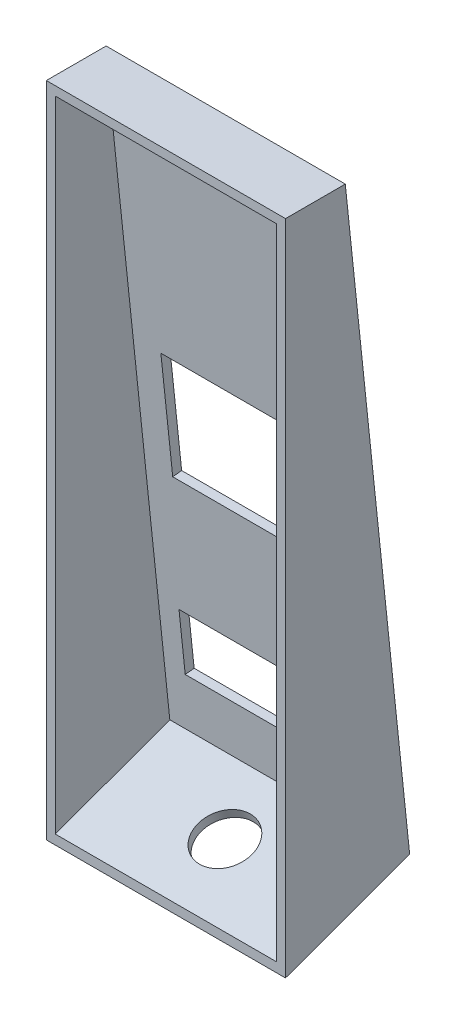
SolidWorks part; units mm, degrees
ref_plane "Front Plane" through (0, 0, 0) normal (0, 0, 1) x (1, 0, 0)
ref_plane "Top Plane" through (0, 0, 0) normal (0, 1, 0) x (1, 0, 0)
ref_plane "Right Plane" through (0, 0, 0) normal (1, 0, 0) x (0, 0, -1)
sketch "Sketch2" plane through (0, 0, 0) normal (0, 0, 1) x (1, 0, 0)
  line L1 (0, -2930) -> (-400, -2930)
  line L2 (0, -2930) -> (0, -4030)
  line L3 (0, -4030) -> (-400, -4030)
  line L4 (-400, -2930) -> (-400, -4030)
  point P4 (-250, 505)
  point P7 (0, 0)
  point P8 (0, 0)
  point P9 (0, 0)
sketch "Sketch3" plane through (0, -2930, 0) normal (0, 1, 0) x (1, 0, 0)
  line L0 (0, -300) -> (0, 0) construction
  line L1 (-400, -300) -> (0, -300)
  line L2 (-400, -300) -> (-400, 100)
  line L3 (-400, 100) -> (0, 100)
  line L4 (0, -300) -> (0, 100)
  line L5 (-400, -300) -> (0, 100) construction
  line L6 (-400, 100) -> (0, -300) construction
  point P4 (-200, -100)
  dimension "D1" = 400
sketch "Sketch5" plane through (0, 0, 0) normal (0, 0, -1) x (-1, 0, 0)
  line L0 (400, -2930) -> (400, -4030) construction
  line L1 (0, -2930) -> (400, -2930)
  line L2 (0, -2930) -> (0, -3880)
  line L3 (0, -3880) -> (400, -3880)
  line L4 (400, -2930) -> (400, -3880)
  line L5 (0, -2930) -> (400, -3880) construction
  line L6 (0, -3880) -> (400, -2930) construction
  point P4 (200, -3405)
  dimension "D1" = 950
ref_plane "Plane1" through (0, -21.6182, 205.6832) normal (0, 0.1045, -0.9945) x (1, 0, 0)
sketch "Sketch4" plane through (0, -21.6182, 205.6832) normal (0, 0.1045, -0.9945) x (1, 0, 0)
  line L0 (-400, 2913.9492) -> (-400, 4007.9232) construction
  line L1 (0, 2924.402) -> (-400, 2924.402)
  line L2 (0, 2924.402) -> (0, 3954.402)
  line L3 (0, 3954.402) -> (-400, 3954.402)
  line L4 (-400, 2924.402) -> (-400, 3954.402)
  line L7 (0, 2913.9492) -> (0, 4007.9232) construction
  line L8 (-400, 2924.402) -> (0, 2924.402) construction
  point P4 (-200, -616.3498)
  point P5 (0, -112.6957)
  point P6 (0, 0)
  point P7 (0, 0)
  point P8 (0, 0)
  point P15 (0, 0)
  point P16 (-385, 1118.8822)
  dimension "D1" = 1030
loft "Loft1" add profiles "Sketch4", "Sketch2"
sketch "Sketch6" plane through (0, -21.6182, 205.6832) normal (0, 0.1045, -0.9945) x (-1, 0, 0)
  line L0 (200, 53.5212) -> (200, 50053.5212) construction
  line L1 (51.5, -3344.402) -> (348.5, -3344.402) construction
  line L2 (51.5, -3344.402) -> (51.5, -3554.402) construction
  line L3 (51.5, -3554.402) -> (348.5, -3554.402) construction
  line L4 (348.5, -3344.402) -> (348.5, -3554.402) construction
  line L5 (50, -3854.402) -> (350, -3854.402)
  line L6 (50, -3854.402) -> (50, -3754.402)
  line L7 (61.5, -3354.402) -> (338.5, -3354.402)
  line L8 (61.5, -3354.402) -> (61.5, -3544.402)
  line L9 (61.5, -3544.402) -> (338.5, -3544.402)
  line L10 (338.5, -3354.402) -> (338.5, -3544.402)
  line L11 (50, -3754.402) -> (350, -3754.402)
  line L12 (350, -3854.402) -> (350, -3754.402)
  line L13 (50, -3854.402) -> (350, -3754.402) construction
  line L14 (50, -3754.402) -> (350, -3854.402) construction
  line L15 (0, -3954.402) -> (400, -3954.402) construction
  point P4 (572.6293, 774.493)
  point P9 (0, 0)
  point P14 (200, -3804.402)
  point P19 (200, -3954.402)
  point P20 (200, -3754.402)
  point P21 (200, -3354.402)
  point P22 (535.1913, 845.8091)
  dimension "D1" = 297
  dimension "D2" = 210
  dimension "D3" = 10
  dimension "D4" = 10
  dimension "D5" = 10
  dimension "D6" = 10
  dimension "D7" = 100
  dimension "D8" = 300
  dimension "D9" = 200
  dimension "D10" = 100
extrude "Cut-Extrude1" cut sketch "Sketch6" against normal blind 50 contours L5 L12 L11 L6 | L8 L9 L10 L7
shell "Shell1" thickness 15
sketch "Sketch7" plane through (0, -3557.9315, -1295.9889) normal (0, -0.9396, -0.3423) x (1, 0, 0)
  line L0 (-200, 1379.2882) -> (-200, 1158.2763) construction
  line L1 (-400, 1379.2882) -> (0, 1379.2882) construction
  line L2 (0, 1158.2763) -> (-400, 1158.2763) construction
  circle A0 centre (-200, 1268.7822) radius 45
  point P8 (0, 0)
  point P9 (-200, 1268.7822)
  dimension "D1" = 90
extrude "Cut-Extrude2" cut sketch "Sketch7" against normal blind 50
